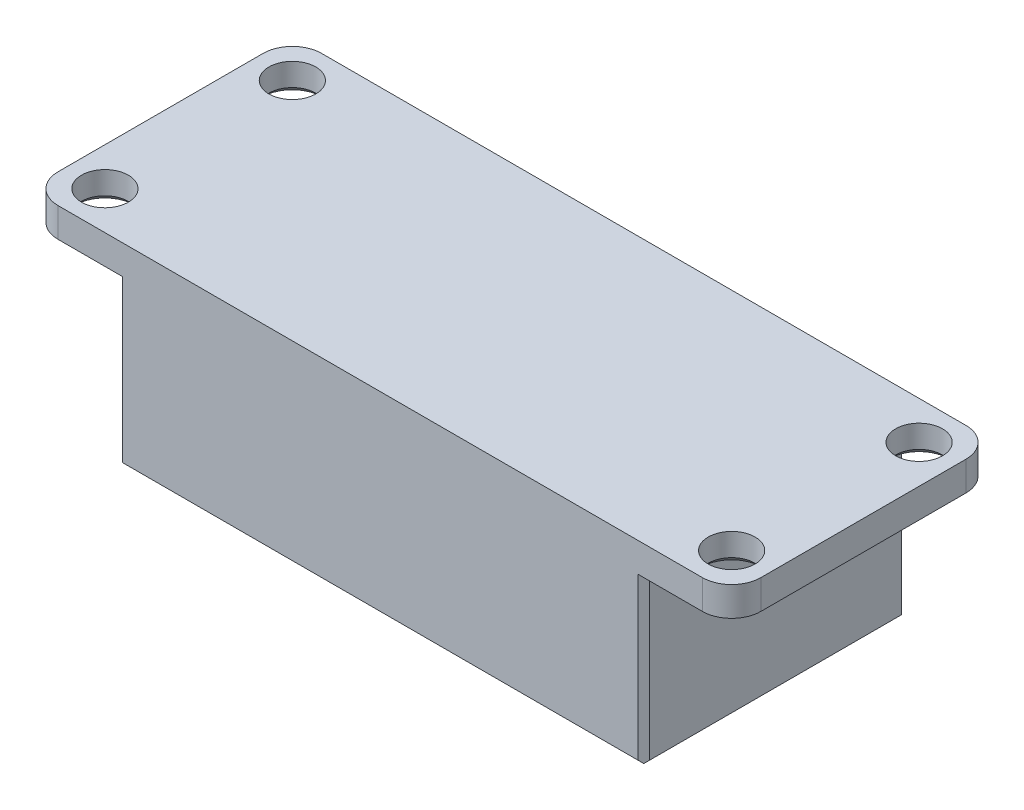
SolidWorks part; units mm, degrees
material "橡胶"
ref_plane "前视基准面" through (0, 0, 0) normal (0, 0, 1) x (1, 0, 0)
ref_plane "上视基准面" through (0, 0, 0) normal (0, 1, 0) x (1, 0, 0)
ref_plane "右视基准面" through (0, 0, 0) normal (1, 0, 0) x (0, 0, -1)
sketch "草图1" plane through (0, 0, 0) normal (0, 1, 0) x (1, 0, 0)
  line L1 (-9, 4.5) -> (9, 4.5)
  line L2 (-9, 4.5) -> (-9, -4.5)
  line L3 (-9, -4.5) -> (9, -4.5)
  line L4 (9, 4.5) -> (9, -4.5)
  line L5 (-9, 4.5) -> (9, -4.5) construction
  line L6 (-9, -4.5) -> (9, 4.5) construction
  point P0 (0, 0)
  dimension "D1" = 9
  dimension "D2" = 18
extrude "凸台-拉伸1" add sketch "草图1" along normal blind 6 contours L3 L4 L1 L2
sketch "草图2" plane through (0, 6, 0) normal (0, 1, 0) x (1, 0, 0)
  line L0 (-9, 4.5) -> (-9, -4.5) construction
  line L1 (12, 4.5) -> (-12, 4.5)
  line L2 (12, 4.5) -> (12, -4.5)
  line L3 (12, -4.5) -> (-12, -4.5)
  line L4 (-12, 4.5) -> (-12, -4.5)
  line L5 (12, 4.5) -> (-12, -4.5) construction
  line L6 (12, -4.5) -> (-12, 4.5) construction
  line L7 (-9, -4.5) -> (9, -4.5) construction
  point P0 (0, 0)
  dimension "D1" = 9
  dimension "D2" = 24
  dimension "D3" = 3
extrude "凸台-拉伸2" add sketch "草图2" along normal blind 1
fillet "圆角1" radius 1 4 edges at (12, 6.5, -4.5) (12, 6.5, 4.5) (-12, 6.5, 4.5) (-12, 6.5, -4.5)
chamfer "倒角1" distance 0.5 angle 45 4 edges at (0, 0, 4.5) (9, 0, 0) (0, 0, -4.5) (-9, 0, 0)
chamfer "倒角2" distance 0.2 angle 45 4 edges at (-9, 3.25, -4.5) (-9, 3.25, 4.5) (9, 3.25, 4.5) (9, 3.25, -4.5)
sketch "草图3" plane through (0, 6, 0) normal (0, -1, 0) x (1, 0, 0)
  line L0 (-12, -3.5) -> (-12, 3.5) construction
  line L1 (10.7, 3.2) -> (-10.7, 3.2)
  line L2 (10.7, 3.2) -> (10.7, -3.2)
  line L3 (10.7, -3.2) -> (-10.7, -3.2)
  line L4 (-10.7, 3.2) -> (-10.7, -3.2)
  line L5 (10.7, 3.2) -> (-10.7, -3.2) construction
  line L6 (10.7, -3.2) -> (-10.7, 3.2) construction
  line L7 (-11, 4.5) -> (-8.8, 4.5) construction
  point P0 (0, 0)
  point P10 (-9.9, 4.5)
  dimension "D1" = 1.3
  dimension "D2" = 1.3
hole_wizard "M2 螺纹孔1" positions "草图4" profile "草图5" tap size "M2" standard "GB" end condition up to next
sketch "草图4" plane through (0, 6, 0) normal (0, -1, 0) x (-1, 0, 0)
  point P0 (10.7, 3.2)
  point P3 (10.7, -3.2)
  point P6 (-10.7, -3.2)
  point P9 (-10.7, 3.2)
sketch "草图5" plane through (-10.7, 6, -3.2) normal (1, 0, 0) x (0, 0, -1)
  line L0 (0, 0) -> (0, 1)
  line L1 (0, 1) -> (0.8, 1)
  line L2 (0.8, 1) -> (0.8, 0.225)
  line L3 (0.8, 0.225) -> (1.025, 0)
  line L5 (1.025, 0) -> (0, 0)
  line L6 (-0.8, 0.225) -> (-1.025, 0) construction
  line L11 (0, -6.35) -> (0, 107.95) construction
  dimension "通孔螺纹孔钻头直径" = 1.6
  dimension "通孔螺纹孔钻头深度" = 1
  dimension "近端锥形沉头孔直径" = 2.05
  dimension "近端锥形沉头孔角度" = 90
cosmetic thread "孔螺蚊线1" parameters "D2"=2
cosmetic thread "孔螺蚊线2" parameters "D2"=2
cosmetic thread "孔螺蚊线3" parameters "D2"=2
cosmetic thread "孔螺蚊线4" parameters "D2"=2
